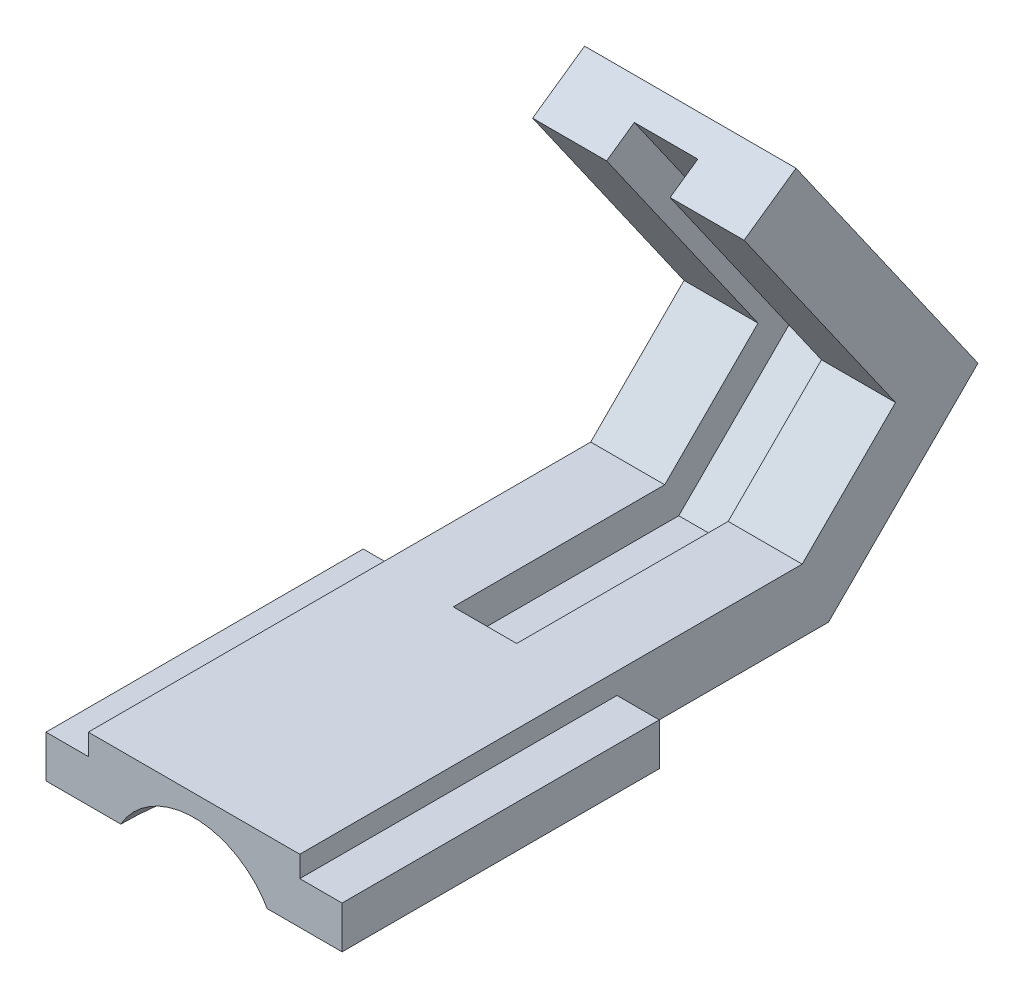
SolidWorks part; units mm, degrees
material "Cast Alloy Steel"
ref_plane "Front Plane" through (0, 0, 0) normal (0, 0, 1) x (1, 0, 0)
ref_plane "Top Plane" through (0, 0, 0) normal (0, 1, 0) x (1, 0, 0)
ref_plane "Right Plane" through (0, 0, 0) normal (1, 0, 0) x (0, 0, -1)
sketch "Sketch2" plane through (0, 0, 0) normal (1, 0, 0) x (0, 0, -1)
  line L0 (0, 0) -> (125, 0)
  line L1 (125, 0) -> (160.3553, 35.3553)
  line L2 (160.3553, 35.3553) -> (117.3371, 96.7917)
  line L3 (117.3371, 96.7917) -> (105.0498, 88.1881)
  line L4 (105.0498, 88.1881) -> (140.8487, 37.0619)
  line L5 (140.8487, 37.0619) -> (118.7868, 15)
  line L6 (118.7868, 15) -> (0, 15)
  line L7 (0, 15) -> (0, 0)
  dimension "D1" = 15
  dimension "D2" = 75
  dimension "D3" = 50
  dimension "D4" = 15
  dimension "D5" = 15
  dimension "D6" = 125
  dimension "D7" = 225
  dimension "D8" = 260
extrude "Boss-Extrude2" add sketch "Sketch2" along normal mid plane 50
sketch "Sketch3" plane through (0, 0, 0) normal (1, 0, 0) x (0, 0, -1)
  line L0 (111.603, 92.7767) -> (151.2523, 36.1518)
  line L1 (117.3371, 96.7917) -> (105.0498, 88.1881) construction
  line L2 (151.2523, 36.1518) -> (122.1005, 7)
  line L3 (122.1005, 7) -> (68.7868, 7)
  line L4 (68.7868, 7) -> (68.7868, 15)
  line L5 (118.7868, 15) -> (0, 15) construction
  line L6 (68.7868, 15) -> (118.7868, 15)
  line L7 (118.7868, 15) -> (140.8487, 37.0619)
  line L8 (140.8487, 37.0619) -> (105.0498, 88.1881)
  line L9 (105.0498, 88.1881) -> (111.603, 92.7767)
  dimension "D1" = 8
  dimension "D2" = 8
  dimension "D3" = 8
  dimension "D4" = 50
extrude "Cut-Extrude1" cut sketch "Sketch3" against normal mid plane 15
sketch "Sketch4" plane through (0, 0, 0) normal (0, 1, 0) x (1, 0, 0)
  line L0 (0, -53.2355) -> (0, 53.2355) construction
  line L1 (-25, 0) -> (-35, 0)
  line L2 (-25, 0) -> (-25, 75)
  line L3 (-25, 75) -> (-35, 75)
  line L4 (-35, 0) -> (-35, 75)
  line L5 (25, 0) -> (35, 0)
  line L6 (25, 0) -> (25, 75)
  line L7 (25, 75) -> (35, 75)
  line L8 (35, 0) -> (35, 75)
  dimension "D1" = 75
  dimension "D2" = 10
extrude "Boss-Extrude3" add sketch "Sketch4" along normal blind 10
sketch "Sketch8" plane through (0, 0, 0) normal (1, 0, 0) x (0, 0, -1)
  line L0 (0, 0) -> (0, 10)
  line L1 (0, 0) -> (75, 0) construction
  line L2 (37.4166, 0) -> (0, 0)
  line L3 (0, -10) -> (23.5016, -10) construction
  line L4 (75, 10) -> (0, 10) construction
  arc A0 (0, 10) -> (37.4166, 0) centre (0, -65) cw
  dimension "D1" = 75
  dimension "D2" = 20
revolve "Cut-Revolve5" cut sketch "Sketch8" angle 360 about L3
